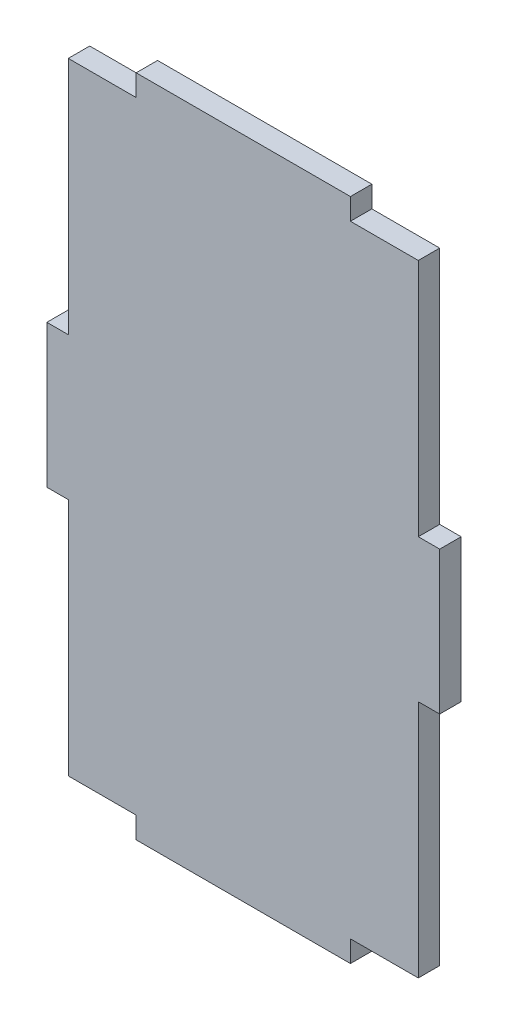
SolidWorks part; units mm, degrees
ref_plane "Front Plane" through (0, 0, 0) normal (0, 0, 1) x (1, 0, 0)
ref_plane "Top Plane" through (0, 0, 0) normal (0, 1, 0) x (1, 0, 0)
ref_plane "Right Plane" through (0, 0, 0) normal (1, 0, 0) x (0, 0, -1)
sketch "Sketch1" plane through (0, 0, 0) normal (0, 0, 1) x (1, 0, 0)
  line L1 (-27.5, 46.5) -> (27.5, 46.5)
  line L2 (-27.5, 46.5) -> (-27.5, -46.5)
  line L3 (-27.5, -46.5) -> (27.5, -46.5)
  line L4 (27.5, 46.5) -> (27.5, -46.5)
  line L5 (-27.5, 46.5) -> (27.5, -46.5) construction
  line L6 (-27.5, -46.5) -> (27.5, 46.5) construction
  point P0 (0, 0)
  dimension "D1" = 55
  dimension "D2" = 93
extrude "Boss-Extrude1" add sketch "Sketch1" along normal blind 3
sketch "Sketch2" plane through (0, 0, 3) normal (0, 0, 1) x (1, 0, 0)
  line L0 (0, 46.5) -> (0, -46.5) construction
  line L5 (27.5, 46.5) -> (-27.5, 46.5) construction
  line L6 (-27.5, -46.5) -> (27.5, -46.5) construction
  line L7 (-27.5, 0) -> (27.5, 0) construction
  line L27 (-27.5, 46.5) -> (-19.5, 46.5)
  line L28 (-27.5, 46.5) -> (-27.5, 10)
  line L29 (-27.5, 10) -> (-24.5, 10)
  line L30 (-24.5, 43.5) -> (-24.5, 10)
  line L31 (-19.5, 46.5) -> (-15, 46.5)
  line L33 (-24.5, 43.5) -> (-15, 43.5)
  line L34 (-15, 46.5) -> (-15, 43.5)
  line L35 (-27.5, 46.5) -> (-27.5, -46.5) construction
  line L36 (27.5, -46.5) -> (27.5, 46.5) construction
  line L38 (-27.5, -46.5) -> (-27.5, -10)
  line L39 (-27.5, -10) -> (-24.5, -10)
  line L40 (-24.5, -43.5) -> (-24.5, -10)
  line L41 (-24.5, -43.5) -> (-15, -43.5)
  line L42 (-15, -46.5) -> (-15, -43.5)
  line L43 (-19.5, -46.5) -> (-15, -46.5)
  line L44 (-27.5, -46.5) -> (-19.5, -46.5)
  line L45 (27.5, -46.5) -> (19.5, -46.5)
  line L46 (19.5, -46.5) -> (15, -46.5)
  line L47 (15, -46.5) -> (15, -43.5)
  line L48 (24.5, -43.5) -> (15, -43.5)
  line L49 (24.5, -43.5) -> (24.5, -10)
  line L50 (27.5, -10) -> (24.5, -10)
  line L51 (27.5, -46.5) -> (27.5, -10)
  line L52 (27.5, 46.5) -> (27.5, 10)
  line L53 (27.5, 10) -> (24.5, 10)
  line L54 (24.5, 43.5) -> (24.5, 10)
  line L55 (24.5, 43.5) -> (15, 43.5)
  line L56 (15, 46.5) -> (15, 43.5)
  line L57 (19.5, 46.5) -> (15, 46.5)
  line L58 (27.5, 46.5) -> (19.5, 46.5)
  dimension "D1" = 9.5
  dimension "D2" = 36.5
  dimension "D3" = 3
  dimension "D4" = 3
extrude "Cut-Extrude2" cut sketch "Sketch2" against normal blind 3
